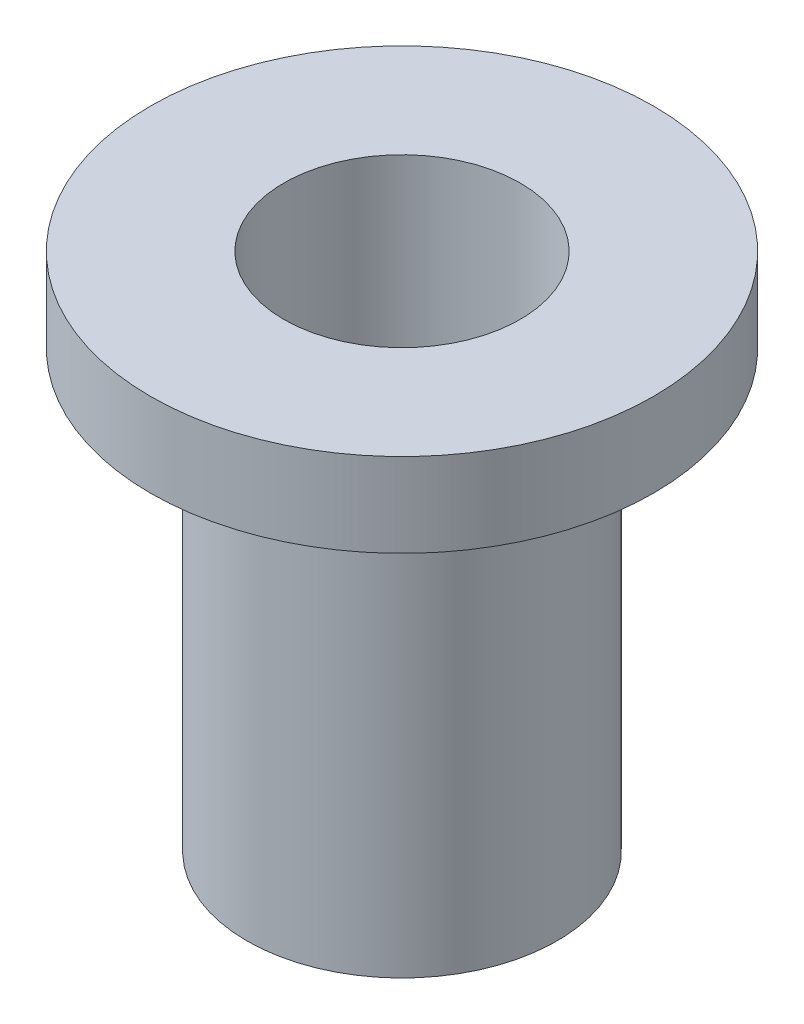
SolidWorks part; units mm, degrees
ref_plane "Front Plane" through (0, 0, 0) normal (0, 0, 1) x (1, 0, 0)
ref_plane "Top Plane" through (0, 0, 0) normal (0, 1, 0) x (1, 0, 0)
ref_plane "Right Plane" through (0, 0, 0) normal (1, 0, 0) x (0, 0, -1)
sketch "Sketch1" plane through (0, 0, 0) normal (0, 0, 1) x (1, 0, 0)
  line L0 (0, 0) -> (0, 353.6557) construction
  line L2 (1.7907, 193.96) -> (2.3495, 193.96)
  line L5 (2.3495, 193.96) -> (2.3495, 200.564)
  line L6 (1.7907, 201.834) -> (3.81, 201.834)
  line L7 (1.7907, 201.834) -> (1.7907, 193.96)
  line L8 (2.3495, 200.564) -> (3.81, 200.564)
  line L9 (3.81, 201.834) -> (3.81, 200.564)
  dimension "D1" = 1.7907
  dimension "D2" = 2.3495
  dimension "D3" = 3.81
  dimension "D4" = 1.27
  dimension "D5" = 6.604
revolve "Revolve1" add sketch "Sketch1" angle 360 about L0
